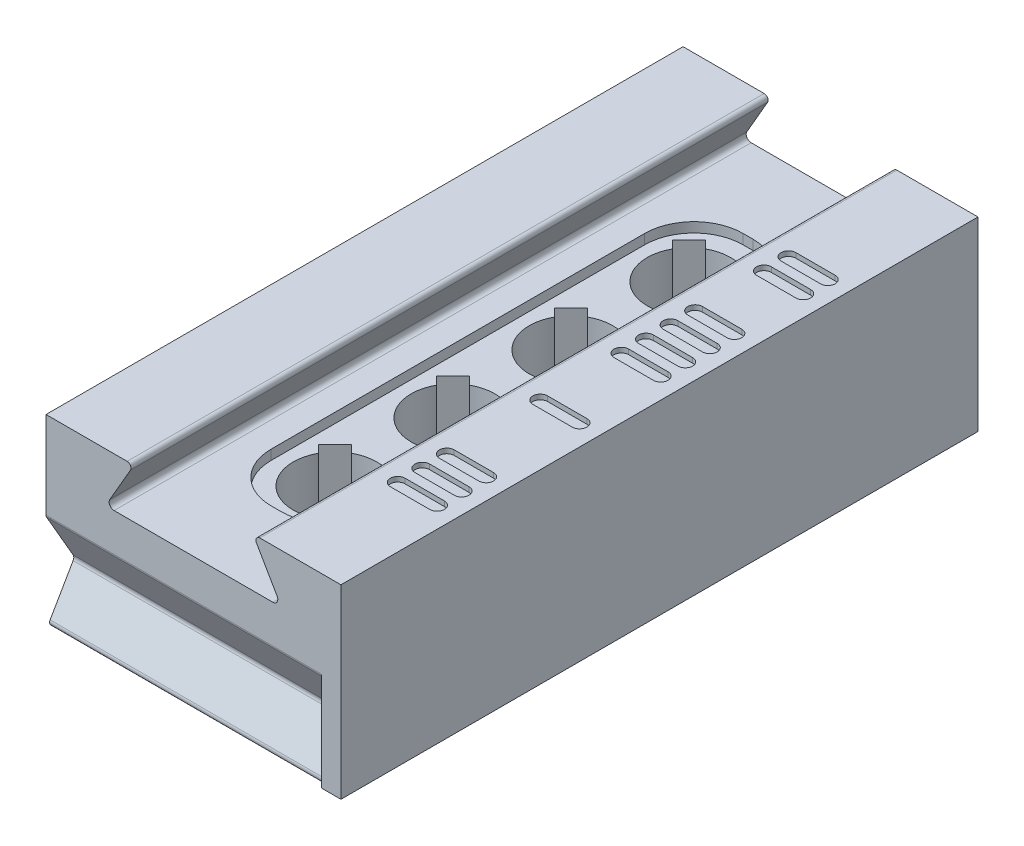
SolidWorks part; units mm, degrees
ref_plane "Front Plane" through (0, 0, 0) normal (0, 0, 1) x (1, 0, 0)
ref_plane "Top Plane" through (0, 0, 0) normal (0, 1, 0) x (1, 0, 0)
ref_plane "Right Plane" through (0, 0, 0) normal (1, 0, 0) x (0, 0, -1)
sketch "Sketch1" plane through (0, 0, 0) normal (1, 0, 0) x (0, 0, -1)
  line L0 (0, 0) -> (0, -19) construction
  line L1 (32.5, -19) -> (-32.5, -19) construction
  line L2 (-32.5, -19) -> (-29.6132, -14) construction
  line L3 (32.5, -19) -> (29.6132, -14) construction
  line L4 (-29.6132, -14) -> (-32.5, -9) construction
  line L5 (29.6132, -14) -> (32.5, -9) construction
  line L6 (-32.5, -9) -> (-32.5, 0) construction
  line L7 (32.5, -9) -> (32.5, 0) construction
  line L8 (-32.5, 0) -> (32.5, 0) construction
  line L9 (32.4, -8.9732) -> (32.4, 0)
  line L10 (29.4978, -14) -> (32.4, -8.9732)
  line L11 (32.3268, -18.9) -> (29.4978, -14)
  line L12 (32.3268, -18.9) -> (-32.3268, -18.9)
  line L13 (-32.3268, -18.9) -> (-29.4978, -14)
  line L14 (-29.4978, -14) -> (-32.4, -8.9732)
  line L15 (-32.4, -8.9732) -> (-32.4, 0)
  line L16 (-32.4, 0) -> (32.4, 0)
  dimension "D1" = 19
  dimension "D2" = 65
  dimension "D3" = 5
  dimension "D4" = 60
  dimension "D5" = 0.1
extrude "Boss-Extrude1" add sketch "Sketch1" along normal mid plane 30
sketch "Sketch2" plane through (0, 0, 0) normal (0, 0, 1) x (1, 0, 0)
  line L0 (0, 0) -> (0, -5) construction
  line L1 (8.9434, -5) -> (-8.9434, -5)
  line L2 (-8.9434, -5) -> (-6.0566, 0)
  line L3 (15, 0) -> (-15, 0) construction
  line L4 (8.9434, -5) -> (6.0566, 0)
  line L5 (-6.0566, 0) -> (0, 0)
  line L6 (0, 0) -> (6.0566, 0)
  line L7 (-8.9434, -5) -> (-15, -5) construction
  line L8 (-15, 0) -> (-15, -8.9732) construction
  dimension "D1" = 5
  dimension "D2" = 60
extrude "Cut-Extrude1" cut sketch "Sketch2" against normal through all both and the other way through all
fillet "Fillet1" radius 0.4 6 edges at (0, -18.9, -32.3268) (0, -8.9732, -32.4) (0, -8.9732, 32.4) (0, -18.9, 32.3268) (6.0566, 0, 0) (-6.0566, 0, 0)
fillet "Fillet2" radius 0.5 4 edges at (0, -14, 29.4978) (0, -14, -29.4978) (8.9434, -5, 0) (-8.9434, -5, 0)
sketch "Sketch3" plane through (0, -5, 0) normal (0, 1, 0) x (1, 0, 0)
  line L0 (-6.7494, 0) -> (6.7494, 0) construction
  line L1 (-6.7494, -32.4) -> (-6.7494, 32.4) construction
  line L2 (6.7494, 32.4) -> (6.7494, -32.4) construction
  line L3 (0, 18) -> (0, 6) construction
  line L4 (0, -18) -> (0, -6) construction
  line L5 (0, 6) -> (0, -6) construction
  circle A0 centre (0, 18) radius 4.25
  circle A1 centre (0, -18) radius 4.25
  circle A2 centre (0, 6) radius 4.25
  circle A3 centre (0, -6) radius 4.25
  point P11 (0, 0)
  dimension "D1" = 8.5
  dimension "D2" = 12
extrude "Cut-Extrude2" cut sketch "Sketch3" against normal up to next
sketch "Sketch5" plane through (0, -5, 0) normal (0, 1, 0) x (1, 0, 0)
  line L0 (-2.8284, 22.5255) -> (4.5255, 15.1716)
  line L1 (-2.8284, 22.5255) -> (-4.5255, 20.8284)
  line L2 (4.5255, 15.1716) -> (2.8284, 13.4745)
  line L3 (-4.5255, 20.8284) -> (2.8284, 13.4745)
  line L4 (-2.8284, 22.5255) -> (2.8284, 13.4745) construction
  line L5 (4.5255, 15.1716) -> (-4.5255, 20.8284) construction
  line L6 (-2.8284, 10.5255) -> (4.5255, 3.1716)
  line L7 (-2.8284, 10.5255) -> (-4.5255, 8.8284)
  line L8 (4.5255, 3.1716) -> (2.8284, 1.4745)
  line L9 (-4.5255, 8.8284) -> (2.8284, 1.4745)
  line L10 (-2.8284, 10.5255) -> (2.8284, 1.4745) construction
  line L11 (4.5255, 3.1716) -> (-4.5255, 8.8284) construction
  line L12 (-2.8284, -1.4745) -> (4.5255, -8.8284)
  line L13 (-2.8284, -1.4745) -> (-4.5255, -3.1716)
  line L14 (4.5255, -8.8284) -> (2.8284, -10.5255)
  line L15 (-4.5255, -3.1716) -> (2.8284, -10.5255)
  line L16 (-2.8284, -1.4745) -> (2.8284, -10.5255) construction
  line L17 (4.5255, -8.8284) -> (-4.5255, -3.1716) construction
  line L18 (-2.8284, -13.4745) -> (4.5255, -20.8284)
  line L19 (-2.8284, -13.4745) -> (-4.5255, -15.1716)
  line L20 (4.5255, -20.8284) -> (2.8284, -22.5255)
  line L21 (-4.5255, -15.1716) -> (2.8284, -22.5255)
  line L22 (-2.8284, -13.4745) -> (2.8284, -22.5255) construction
  line L23 (4.5255, -20.8284) -> (-4.5255, -15.1716) construction
  line L24 (-8.0774, 32.4) -> (8.0774, 32.4) construction
  circle A0 centre (0, 18) radius 4.25 construction
  circle A1 centre (0, 6) radius 4.25 construction
  circle A2 centre (0, -6) radius 4.25 construction
  circle A3 centre (0, -18) radius 4.25 construction
  point P1 (0, 18)
  point P2 (0, 6)
  point P3 (0, -6)
  point P8 (0, -18)
  dimension "D1" = 45
  dimension "D2" = 2.4
  dimension "D3" = 10.4
extrude "Cut-Extrude3" cut sketch "Sketch5" against normal offset from surface (12.9 mm away) 1 up to face at (0, -18.9, 22.25)
sketch "Sketch6" plane through (0, -5, 0) normal (0, 1, 0) x (1, 0, 0)
  line L1 (5.5, 24) -> (-5.5, 24)
  line L2 (5.5, 24) -> (5.5, -24)
  line L3 (5.5, -24) -> (-5.5, -24)
  line L4 (-5.5, 24) -> (-5.5, -24)
  line L5 (5.5, 24) -> (-5.5, -24) construction
  line L6 (5.5, -24) -> (-5.5, 24) construction
  point P0 (0, 0)
  dimension "D1" = 11
  dimension "D2" = 48
extrude "Cut-Extrude4" cut sketch "Sketch6" against normal blind 1
fillet "Fillet3" radius 5 4 edges at (-5.5, -5.5, 24) (5.5, -5.5, 24) (5.5, -5.5, -24) (-5.5, -5.5, -24)
chamfer "Chamfer1" distance 0.5 angle 45 4 edges at (0, -18.9, -13.75) (0, -18.9, -1.75) (0, -18.9, 10.25) (0, -18.9, 22.25)
sketch "Sketch8" plane through (15, 0, 0) normal (1, 0, 0) x (0, 0, -1)
  line L0 (-32.4, -8.866) -> (-32.4, -18.9)
  line L1 (-31.634, -18.9) -> (-32.4, -18.9)
  line L2 (32.4, -8.866) -> (32.4, -18.9)
  line L3 (32.4, -18.9) -> (31.634, -18.9)
  line L8 (-31.634, -18.9) -> (31.634, -18.9)
  line L9 (31.9804, -18.3) -> (29.6421, -14.25)
  line L10 (29.6421, -13.75) -> (32.3464, -9.066)
  line L11 (32.4, -8.866) -> (32.4, 0)
  line L12 (32.4, 0) -> (-32.4, 0)
  line L13 (-32.4, 0) -> (-32.4, -8.866)
  line L14 (-32.3464, -9.066) -> (-29.6421, -13.75)
  line L15 (-29.6421, -14.25) -> (-31.9804, -18.3)
  line L16 (-31.634, -18.9) -> (31.634, -18.9)
  line L19 (32.4, -8.866) -> (32.4, 0)
  line L20 (32.4, 0) -> (-32.4, 0)
  line L21 (-32.4, 0) -> (-32.4, -8.866)
  arc A6 (31.634, -18.9) -> (31.9804, -18.3) centre (31.634, -18.5) ccw
  arc A7 (29.6421, -13.75) -> (29.6421, -14.25) centre (30.0751, -14) ccw
  arc A8 (32.3464, -9.066) -> (32.4, -8.866) centre (32, -8.866) ccw
  arc A9 (-32.4, -8.866) -> (-32.3464, -9.066) centre (-32, -8.866) ccw
  arc A10 (-29.6421, -14.25) -> (-29.6421, -13.75) centre (-30.0751, -14) ccw
  arc A11 (-31.9804, -18.3) -> (-31.634, -18.9) centre (-31.634, -18.5) ccw
  dimension "D1" = 0
extrude "Boss-Extrude2" add sketch "Sketch8" against normal blind 2
sketch "Sketch9" plane through (0, 0, 0) normal (0, 0, 1) x (1, 0, 0)
  line L0 (-15, -18.9) -> (-9, -18.9)
  line L1 (13, -18.9) -> (-15, -18.9) construction
  line L2 (-9, -18.9) -> (-15, -12.9)
  line L3 (-15, -14.25) -> (-15, -18.3) construction
  line L4 (-15, -12.9) -> (-15, -18.9)
  dimension "D1" = 6
extrude "Cut-Extrude5" cut sketch "Sketch9" against normal blind 24 and the other way blind 24
sketch "Sketch10" plane through (0, 0, 0) normal (0, 1, 0) x (1, 0, 0)
  line L0 (0, 18) -> (10.8747, 18) construction
  line L1 (0, 6) -> (10.8747, 6) construction
  line L2 (0, -6) -> (10.8747, -6) construction
  line L3 (0, -18) -> (10.8747, -18) construction
  line L4 (6.7494, 0) -> (15, 0) construction
  line L5 (8.8747, -6) -> (12.8747, -6) construction
  line L6 (8.8747, -5.25) -> (12.8747, -5.25)
  line L7 (8.8747, -6.75) -> (12.8747, -6.75)
  line L8 (8.8747, 16.75) -> (12.8747, 16.75) construction
  line L9 (8.8747, 17.5) -> (12.8747, 17.5)
  line L10 (8.8747, 16) -> (12.8747, 16)
  line L11 (8.8747, 19.25) -> (12.8747, 19.25) construction
  line L12 (8.8747, 20) -> (12.8747, 20)
  line L13 (8.8747, 18.5) -> (12.8747, 18.5)
  line L14 (8.8747, -20.5) -> (12.8747, -20.5) construction
  line L15 (8.8747, -19.75) -> (12.8747, -19.75)
  line L16 (8.8747, -21.25) -> (12.8747, -21.25)
  line L17 (8.8747, -18) -> (12.8747, -18) construction
  line L18 (8.8747, -17.25) -> (12.8747, -17.25)
  line L19 (8.8747, -18.75) -> (12.8747, -18.75)
  line L20 (8.8747, -15.5) -> (12.8747, -15.5) construction
  line L21 (8.8747, -14.75) -> (12.8747, -14.75)
  line L22 (8.8747, -16.25) -> (12.8747, -16.25)
  line L23 (8.8747, 4.75) -> (12.8747, 4.75) construction
  line L24 (8.8747, 5.5) -> (12.8747, 5.5)
  line L25 (8.8747, 4) -> (12.8747, 4)
  line L26 (8.8747, 7.25) -> (12.8747, 7.25) construction
  line L27 (8.8747, 8) -> (12.8747, 8)
  line L28 (8.8747, 6.5) -> (12.8747, 6.5)
  line L29 (8.8747, 9.75) -> (12.8747, 9.75) construction
  line L30 (8.8747, 10.5) -> (12.8747, 10.5)
  line L31 (8.8747, 9) -> (12.8747, 9)
  line L32 (8.8747, 2.25) -> (12.8747, 2.25) construction
  line L33 (8.8747, 3) -> (12.8747, 3)
  line L34 (8.8747, 1.5) -> (12.8747, 1.5)
  line L35 (10.8747, -20.5) -> (10.8747, -18) construction
  line L36 (10.8747, -18) -> (10.8747, -15.5) construction
  line L37 (10.8747, 2.25) -> (10.8747, 4.75) construction
  line L38 (10.8747, 4.75) -> (10.8747, 7.25) construction
  line L39 (10.8747, 7.25) -> (10.8747, 9.75) construction
  line L40 (10.8747, 16.75) -> (10.8747, 19.25) construction
  line L41 (6.7494, 32.4) -> (6.7494, -32.4) construction
  line L42 (15, 32.4) -> (15, -32.4) construction
  arc A0 (8.8747, -5.25) -> (8.8747, -6.75) centre (8.8747, -6) ccw
  arc A1 (12.8747, -6.75) -> (12.8747, -5.25) centre (12.8747, -6) ccw
  arc A2 (8.8747, 17.5) -> (8.8747, 16) centre (8.8747, 16.75) ccw
  arc A3 (12.8747, 16) -> (12.8747, 17.5) centre (12.8747, 16.75) ccw
  arc A4 (8.8747, 20) -> (8.8747, 18.5) centre (8.8747, 19.25) ccw
  arc A5 (12.8747, 18.5) -> (12.8747, 20) centre (12.8747, 19.25) ccw
  arc A6 (8.8747, -19.75) -> (8.8747, -21.25) centre (8.8747, -20.5) ccw
  arc A7 (12.8747, -21.25) -> (12.8747, -19.75) centre (12.8747, -20.5) ccw
  arc A8 (8.8747, -17.25) -> (8.8747, -18.75) centre (8.8747, -18) ccw
  arc A9 (12.8747, -18.75) -> (12.8747, -17.25) centre (12.8747, -18) ccw
  arc A10 (8.8747, -14.75) -> (8.8747, -16.25) centre (8.8747, -15.5) ccw
  arc A11 (12.8747, -16.25) -> (12.8747, -14.75) centre (12.8747, -15.5) ccw
  arc A12 (8.8747, 5.5) -> (8.8747, 4) centre (8.8747, 4.75) ccw
  arc A13 (12.8747, 4) -> (12.8747, 5.5) centre (12.8747, 4.75) ccw
  arc A14 (8.8747, 8) -> (8.8747, 6.5) centre (8.8747, 7.25) ccw
  arc A15 (12.8747, 6.5) -> (12.8747, 8) centre (12.8747, 7.25) ccw
  arc A16 (8.8747, 10.5) -> (8.8747, 9) centre (8.8747, 9.75) ccw
  arc A17 (12.8747, 9) -> (12.8747, 10.5) centre (12.8747, 9.75) ccw
  arc A18 (8.8747, 3) -> (8.8747, 1.5) centre (8.8747, 2.25) ccw
  arc A19 (12.8747, 1.5) -> (12.8747, 3) centre (12.8747, 2.25) ccw
  point P13 (10.8747, -6)
  point P20 (10.8747, 16.75)
  point P27 (10.8747, 19.25)
  point P34 (10.8747, -20.5)
  point P41 (10.8747, -18)
  point P48 (10.8747, -15.5)
  point P55 (10.8747, 4.75)
  point P62 (10.8747, 7.25)
  point P69 (10.8747, 9.75)
  point P76 (10.8747, 2.25)
  point P90 (10.8747, 0)
  point P95 (10.8747, 6)
  point P97 (10.8747, 18)
  dimension "D1" = 1.5
  dimension "D2" = 2.5
  dimension "D3" = 4
extrude "Cut-Extrude6" cut sketch "Sketch10" against normal blind 0.5
